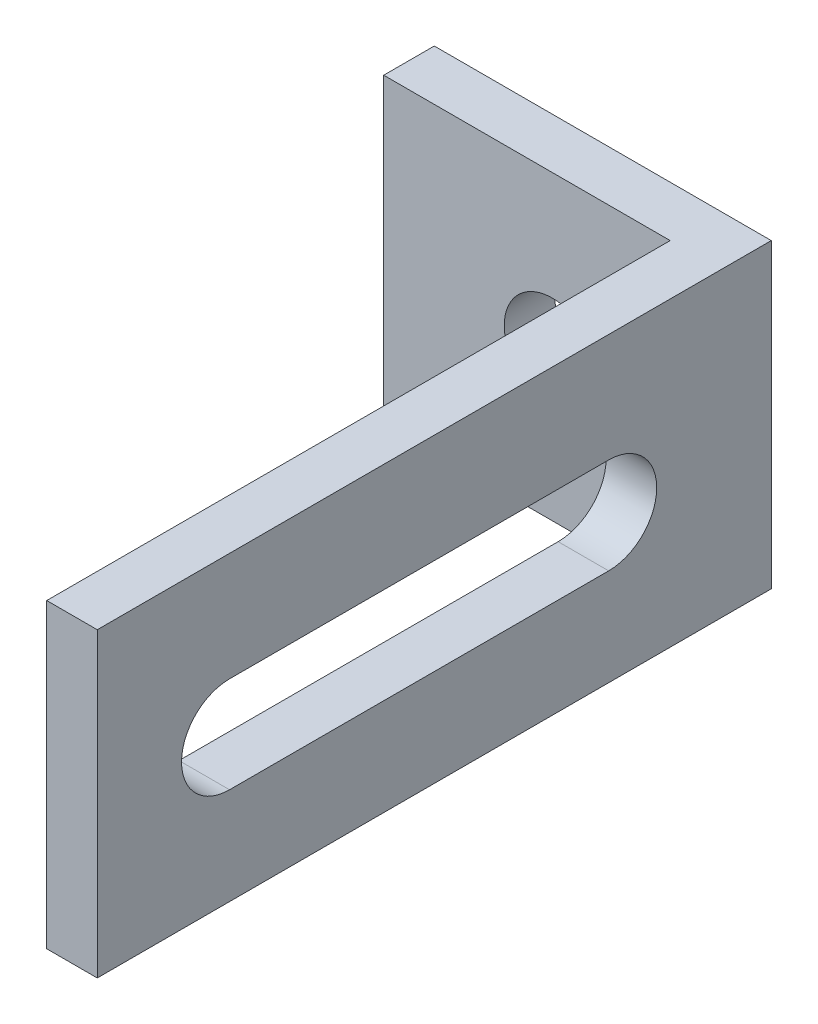
SolidWorks part; units mm, degrees
ref_plane "前视基准面" through (0, 0, 0) normal (0, 0, 1) x (1, 0, 0)
ref_plane "上视基准面" through (0, 0, 0) normal (0, 1, 0) x (1, 0, 0)
ref_plane "右视基准面" through (0, 0, 0) normal (1, 0, 0) x (0, 0, -1)
other "Configuration Table"
sketch "草图1" plane through (0, 0, 0) normal (0, 0, 1) x (1, 0, 0)
  line L1 (-10, -8.95) -> (10, -8.95)
  line L2 (-10, -8.95) -> (-10, 8.95)
  line L3 (-10, 8.95) -> (10, 8.95)
  line L4 (10, -8.95) -> (10, 8.95)
  line L5 (-10, -8.95) -> (10, 8.95) construction
  line L6 (-10, 8.95) -> (10, -8.95) construction
  circle A1 centre (0, -0.35) radius 2.85
  point P0 (0, 0)
  dimension "D3" = 5.7
  dimension "D4" = 10
  dimension "D5" = 8.6
  dimension "D1" = 20
  dimension "D2" = 17.9
extrude "凸台-拉伸1" add sketch "草图1" along normal blind 3
sketch "草图2" plane through (0, 0, 3) normal (0, 0, 1) x (1, 0, 0)
  line L0 (-10, -8.95) -> (10, -8.95) construction
  line L1 (10, 8.95) -> (7, 8.95)
  line L2 (10, 8.95) -> (10, -8.95)
  line L3 (10, -8.95) -> (7, -8.95)
  line L4 (7, 8.95) -> (7, -8.95)
  dimension "D1" = 3
extrude "凸台-拉伸2" add sketch "草图2" along normal blind 37
sketch "草图3" plane through (7, 0, 0) normal (-1, 0, 0) x (0, 0, 1)
  line L0 (32.15, -0.35) -> (9.65, -0.35) construction
  line L1 (32.15, -3.2) -> (9.65, -3.2)
  line L2 (32.15, 2.5) -> (9.65, 2.5)
  line L3 (40, -8.95) -> (3, -8.95) construction
  line L4 (40, 8.95) -> (40, -8.95) construction
  arc A0 (32.15, -3.2) -> (32.15, 2.5) centre (32.15, -0.35) ccw
  arc A1 (9.65, 2.5) -> (9.65, -3.2) centre (9.65, -0.35) ccw
  point P3 (20.9, -0.35)
  point P8 (6.8, -0.35)
  point P9 (35, -0.35)
  point P10 (35.7582, 0)
  point P11 (36.7694, 0)
  point P12 (18.4832, -2.2612)
  point P13 (20.8708, -1.7275)
  dimension "D1" = 5.7
  dimension "D2" = 28.2
  dimension "D3" = 8.6
  dimension "D4" = 5
extrude "切除-拉伸1" cut sketch "草图3" against normal blind 37
